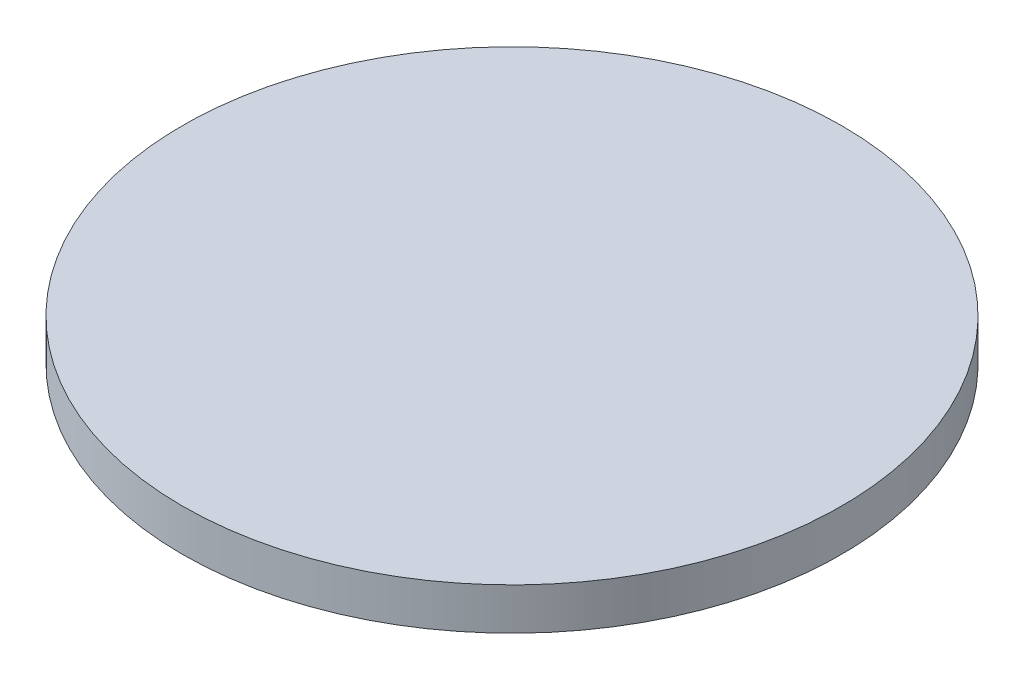
SolidWorks part; units mm, degrees
ref_plane "Front Plane" through (0, 0, 0) normal (0, 0, 1) x (1, 0, 0)
ref_plane "Top Plane" through (0, 0, 0) normal (0, 1, 0) x (1, 0, 0)
ref_plane "Right Plane" through (0, 0, 0) normal (1, 0, 0) x (0, 0, -1)
sketch "Sketch1" plane through (0, 0, 0) normal (0, 1, 0) x (1, 0, 0)
  circle A0 centre (0, 0) radius 50
  dimension "D1" = 100
extrude "Boss-Extrude1" add sketch "Sketch1" along normal blind 6.35
